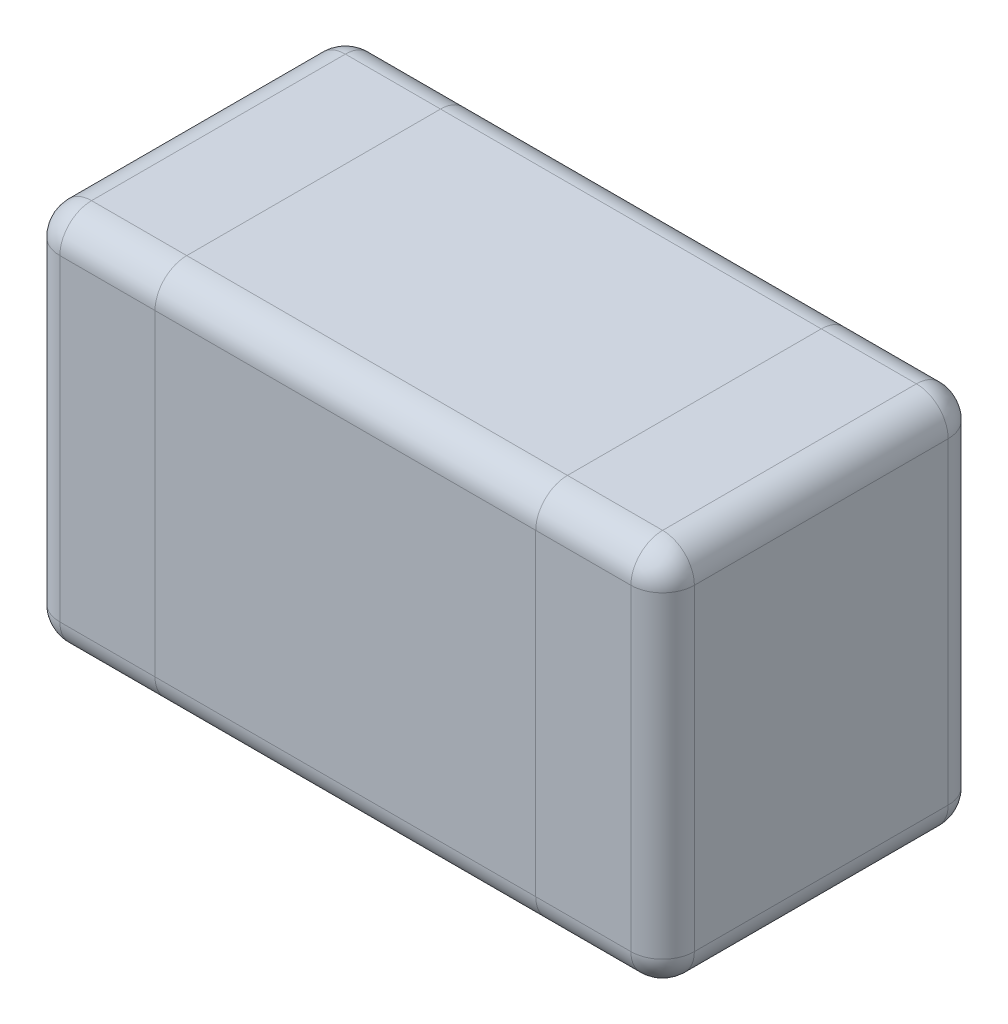
SolidWorks part; units mm, degrees
ref_plane "Front Plane" through (0, 0, 0) normal (0, 0, 1) x (1, 0, 0)
ref_plane "Top Plane" through (0, 0, 0) normal (0, 1, 0) x (1, 0, 0)
ref_plane "Right Plane" through (0, 0, 0) normal (1, 0, 0) x (0, 0, -1)
sketch "Sketch1" plane through (0, 0, 0) normal (0, 1, 0) x (1, 0, 0)
  line L1 (-0.5, -0.25) -> (0.5, -0.25)
  line L2 (-0.5, -0.25) -> (-0.5, 0.25)
  line L3 (-0.5, 0.25) -> (0.5, 0.25)
  line L4 (0.5, -0.25) -> (0.5, 0.25)
  line L5 (-0.5, -0.25) -> (0.5, 0.25) construction
  line L6 (-0.5, 0.25) -> (0.5, -0.25) construction
  point P0 (0, 0)
  dimension "D1" = 1
  dimension "D2" = 0.5
extrude "Extrude1" add sketch "Sketch1" along normal blind 0.6
fillet "Fillet1" radius 0.05 12 edges at (0.5, 0.3, -0.25) (-0.5, 0.3, -0.25) (-0.5, 0.3, 0.25) (0.5, 0.3, 0.25) (0, 0.6, 0.25) (-0.5, 0.6, 0) (0, 0.6, -0.25) (0.5, 0.6, 0) (0, 0, -0.25) (-0.5, 0, 0) (0, 0, 0.25) (0.5, 0, 0)
sketch "Sketch2" plane through (0, 0, 0) normal (0, 1, 0) x (1, 0, 0)
  line L0 (-0.45, 0.25) -> (0.45, 0.25) construction
  line L1 (-0.3, -0.25) -> (0.3, -0.25)
  line L2 (-0.3, -0.25) -> (-0.3, 0.25)
  line L3 (-0.3, 0.25) -> (0.3, 0.25)
  line L4 (0.3, -0.25) -> (0.3, 0.25)
  line L5 (0.45, -0.25) -> (-0.45, -0.25) construction
  line L6 (0, 0.2) -> (0, -0.6635) construction
  line L7 (0.45, 0.2) -> (-0.45, 0.2) construction
  line L9 (-0.5, -0.2) -> (-0.5, 0.2) construction
  dimension "D1" = 0.2
split line "Split Line3"
